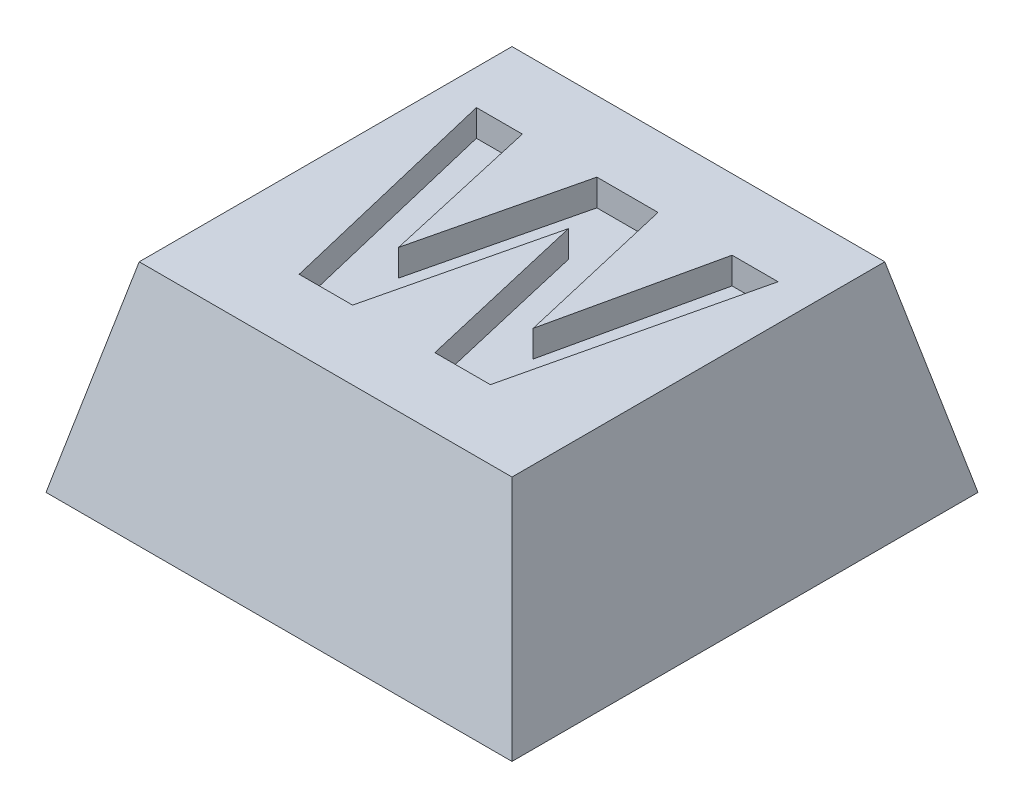
SolidWorks part; units mm, degrees
ref_plane "Front Plane" through (0, 0, 0) normal (0, 0, 1) x (1, 0, 0)
ref_plane "Top Plane" through (0, 0, 0) normal (0, 1, 0) x (1, 0, 0)
ref_plane "Right Plane" through (0, 0, 0) normal (1, 0, 0) x (0, 0, -1)
sketch "Sketch1" plane through (0, 0, 0) normal (0, 1, 0) x (1, 0, 0)
  line L1 (0, 0) -> (7, 0)
  line L2 (0, 0) -> (0, 7)
  line L3 (0, 7) -> (7, 7)
  line L4 (7, 0) -> (7, 7)
  dimension "D1" = 7
  dimension "D2" = 7
extrude "Boss-Extrude1" add sketch "Sketch1" along normal blind 3
sketch "Sketch2" plane through (0, 0, 0) normal (0, 0, 1) x (1, 0, 0)
  line L0 (0, 0) -> (0.7, 3)
  line L1 (0, 3) -> (7, 3) construction
  line L2 (0.7, 3) -> (0, 3)
  line L3 (0, 3) -> (0, 0)
  line L4 (7, 0) -> (6.3, 3)
  line L5 (6.3, 3) -> (7, 3)
  line L6 (7, 3) -> (7, 0)
  dimension "D1" = 0.7
  dimension "D2" = 0.7
extrude "Cut-Extrude1" cut sketch "Sketch2" against normal blind 7
sketch "Sketch3" plane through (0, 0, 0) normal (1, 0, 0) x (0, 0, -1)
  line L0 (0, 0) -> (0.7, 3)
  line L1 (7, 3) -> (0, 3) construction
  line L2 (0.7, 3) -> (0, 3)
  line L3 (0, 3) -> (0, 0)
  line L4 (7, 3) -> (6.3, 3)
  line L5 (6.3, 3) -> (7, 0)
  line L6 (7, 3) -> (7, 0)
  dimension "D1" = 0.7
  dimension "D2" = 0.7
extrude "Cut-Extrude2" cut sketch "Sketch3" along normal blind 11
sketch "Sketch4" plane through (0, 0, 0) normal (0, -1, 0) x (1, 0, 0)
  line L0 (3.5, 0) -> (3.5, -7) construction
  line L1 (0, 0) -> (7, 0) construction
  line L2 (7, -7) -> (0, -7) construction
  line L3 (0, -3.5) -> (7, -3.5) construction
  line L4 (0, -7) -> (0, 0) construction
  line L5 (7, 0) -> (7, -7) construction
  circle A0 centre (3.5, -3.5) radius 1.8
  dimension "D1" = 3.6
extrude "Cut-Extrude3" cut sketch "Sketch4" against normal blind 0.8
sketch "Sketch5" plane through (0, 3, 0) normal (0, 1, 0) x (1, 0, 0)
  text T0 "W" font "Arial" height 3.5
extrude "Cut-Extrude4" cut sketch "Sketch5" against normal blind 0.4
